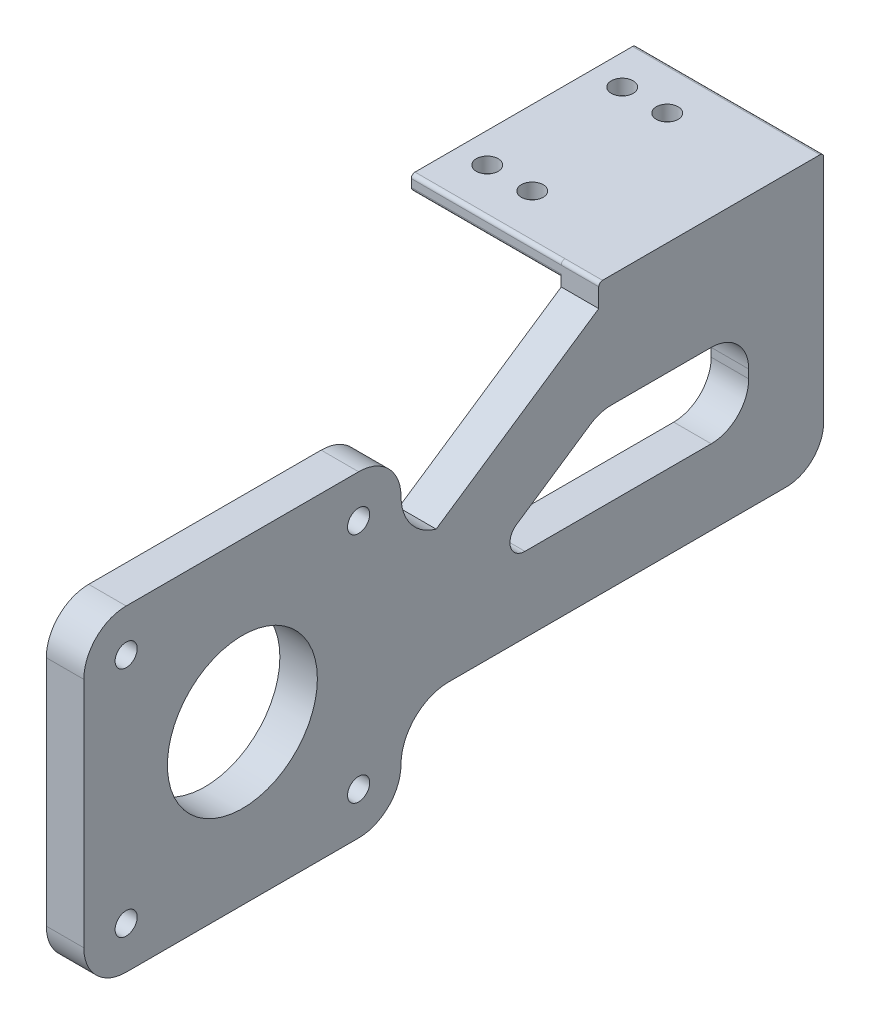
SolidWorks part; units mm, degrees
ref_plane "前视基准面" through (0, 0, 0) normal (0, 0, 1) x (1, 0, 0)
ref_plane "上视基准面" through (0, 0, 0) normal (0, 1, 0) x (1, 0, 0)
ref_plane "右视基准面" through (0, 0, 0) normal (1, 0, 0) x (0, 0, -1)
sketch "草图1" plane through (0, 0, 0) normal (1, 0, 0) x (0, 0, -1)
  line L0 (15.5, 27.49) -> (15.5, -26.0061) construction
  line L1 (-15.5, 21.15) -> (15.5, 21.15)
  line L2 (-21.15, 15.5) -> (-21.15, -15.5)
  line L3 (-15.5, -21.15) -> (15.5, -21.15)
  line L4 (47.6408, 12) -> (67.5191, 12)
  line L5 (-25.5408, 25.5408) -> (23.9603, -23.9603) construction
  line L6 (-23.3332, -23.3332) -> (25.859, 25.859) construction
  line L7 (-40.1945, 0) -> (102.8168, 0) construction
  line L8 (48.0191, 27) -> (77.0191, 27)
  line L9 (47.5191, 23.98) -> (25.8385, 9.3566)
  line L10 (67.5191, 12) -> (67.5191, 0.8691)
  line L11 (47.5191, -9.1309) -> (27.5191, -9.1309)
  line L12 (47.5191, 26.5) -> (47.5191, 23.98)
  line L13 (47.5191, -9.1309) -> (77.5191, -9.1309)
  line L15 (47.5191, -9.1309) -> (77.5191, -9.1309)
  line L16 (77.5191, 26.5) -> (77.5191, -9.1309)
  line L17 (62.5191, 33.18) -> (62.5191, 22.6251) construction
  line L18 (-22.7596, 15.5) -> (21.7018, 15.5) construction
  line L19 (59.5191, 0.8691) -> (67.5191, 0.8691)
  line L20 (-15.5, 22.9461) -> (-15.5, -24.5462) construction
  line L21 (-26.6771, -15.5) -> (22.2596, -15.5) construction
  line L22 (59.5191, 0.8691) -> (53.5191, 0.8691)
  line L23 (53.5191, 0.8691) -> (31.1383, 0.8691)
  line L24 (31.1383, 0.8691) -> (47.6408, 12)
  circle A0 centre (-15.5, 15.5) radius 1.475
  circle A1 centre (15.5, 15.5) radius 1.475
  circle A2 centre (15.5, -15.5) radius 1.475
  circle A3 centre (-15.5, -15.5) radius 1.475
  arc A4 (-15.5, 21.15) -> (-21.15, 15.5) centre (-15.5, 15.5) ccw
  arc A5 (-21.15, -15.5) -> (-15.5, -21.15) centre (-15.5, -15.5) ccw
  arc A6 (21.15, 15.5) -> (15.5, 21.15) centre (15.5, 15.5) ccw
  arc A7 (15.5, -21.15) -> (21.15, -15.5) centre (15.5, -15.5) ccw
  circle A8 centre (0, 0) radius 10
  arc A9 (21.15, 15.5) -> (25.8385, 9.3566) centre (27.5191, 15.5) ccw
  arc A10 (27.5191, -9.1309) -> (21.15, -15.5) centre (27.5191, -15.5) ccw
  arc A11 (48.0191, 27) -> (47.5191, 26.5) centre (48.0191, 26.5) ccw
  arc A14 (77.0191, 27) -> (77.5191, 26.5) centre (77.0191, 26.5) cw
  point P0 (0, 0)
  point P55 (77.5191, 25.49)
  dimension "D1" = 2.95
  dimension "D4" = 31
  dimension "D5" = 20
  dimension "D6" = 12.7383
  dimension "D7" = 3.02
  dimension "D8" = 6.3691
  dimension "D13" = 0.5
  dimension "D16" = 14.5
  dimension "D2" = 42.3
  dimension "D3" = 31
  dimension "D9" = 27
  dimension "D10" = 14.6234
  dimension "D11" = 30
  dimension "D12" = 10
  dimension "D14" = 10
  dimension "D15" = 26.1514
  dimension "D18" = 10
  dimension "D19" = 15
extrude "凸台-拉伸1" add sketch "草图1" along normal blind 5 contours A14 L8 A11 L12 L9 A9 A6 L1 A4 L2 A5 L3 A7 A10 L11 L13 L16 A8 A3 A2 A1 A0 L23 L24 L4 L10 L19 L22
fillet "圆角1" radius 5 1 edges at (2.5, -9.1309, -77.5191)
fillet "圆角2" radius 5 1 edges at (2.5, 12, -67.5191)
fillet "圆角3" radius 5 1 edges at (2.5, 12, -47.6408)
fillet "圆角4" radius 5 1 edges at (2.5, 0.8691, -67.5191)
fillet "圆角5" radius 2 1 edges at (2.5, 0.8691, -31.1383)
sketch "草图4" plane through (0, 0, 0) normal (1, 0, 0) x (0, 0, -1)
  line L1 (77.5191, 27) -> (47.5191, 27)
  line L2 (77.5191, 27) -> (77.5191, 24.98)
  line L3 (77.5191, 24.98) -> (47.5191, 24.98)
  line L4 (47.5191, 27) -> (47.5191, 24.98)
  line L5 (48.0191, 27) -> (77.0191, 27) construction
  line L6 (77.5191, 26.5) -> (77.5191, -4.1309) construction
  line L7 (47.5191, 26.5) -> (47.5191, 23.98) construction
  dimension "D1" = 2.02
extrude "凸台-拉伸2" add sketch "草图4" against normal blind 20
fillet "圆角11" radius 0.5 3 edges at (-10, 27, -47.5191) (0, 27, -47.7691) (0, 26.75, -47.5191)
fillet "圆角12" radius 0.5 3 edges at (0, 27, -77.2691) (0, 26.75, -77.5191) (-10, 27, -77.5191)
sketch "草图5" plane through (0, 0, -77.5191) normal (0, 0, 1) x (1, 0, 0)
  line L2 (0, 24.98) -> (0, -4.1309) construction
  line L10 (0, 14.5877) -> (-18, 24.98)
rib "筋5" sketch "草图5" sketch "草图5" thickness 30 parameters "D1"=30
sketch "草图12" plane through (-20, 0, 0) normal (-1, 0, 0) x (0, 0, 1)
  line L0 (-47.5191, 14.5877) -> (-77.5191, 14.5877) construction
  line L1 (-77.5191, 24.98) -> (-66.5191, 24.98)
  line L2 (-77.5191, 24.98) -> (-77.5191, 14.5877)
  line L3 (-77.5191, 14.5877) -> (-66.5191, 14.5877)
  line L4 (-66.5191, 24.98) -> (-66.5191, 14.5877)
  line L5 (-47.5191, 24.98) -> (-77.5191, 24.98) construction
  line L6 (-58.5191, 24.98) -> (-47.5191, 24.98)
  line L7 (-58.5191, 24.98) -> (-58.5191, 14.5877)
  line L8 (-58.5191, 14.5877) -> (-47.5191, 14.5877)
  line L9 (-47.5191, 24.98) -> (-47.5191, 14.5877)
  line L10 (-47.5191, 24.98) -> (-77.5191, 24.98) construction
  point P16 (-62.5191, 24.98)
  dimension "D1" = 8
  dimension "D2" = 4
extrude "切除-拉伸1" cut sketch "草图12" against normal blind 20
fillet "圆角14" radius 0.5 1 edges at (-10, 24.98, -77.5191)
fillet "圆角15" radius 0.5 1 edges at (-10, 24.98, -47.5191)
sketch "草图14" plane through (0, 0, 0) normal (0, 1, 0) x (1, 0, 0)
  line L0 (-10, 79.5057) -> (-10, 45.387) construction
  line L1 (-16, 79.5057) -> (-16, 44.8987) construction
  line L3 (9.3134, 62.6508) -> (-27.689, 62.6508) construction
  line L5 (11.8285, 71.6508) -> (-37.4632, 71.6508) construction
  line L6 (-37.9968, 53.6508) -> (11.8285, 53.6508) construction
  line L9 (5, 48.0191) -> (5, 77.0191) construction
  line L10 (0, 77.0191) -> (-20, 77.0191) construction
  circle A0 centre (-10, 71.6508) radius 1.46
  circle A1 centre (-16, 71.6508) radius 1.46
  circle A2 centre (-10, 53.6508) radius 1.46
  circle A3 centre (-16, 53.6508) radius 1.46
  dimension "D3" = 2.92
  dimension "D4" = 9
  dimension "D5" = 5.3683
  dimension "D1" = 21
  dimension "D2" = 6
extrude "切除-拉伸2" cut sketch "草图14" along normal blind 44
